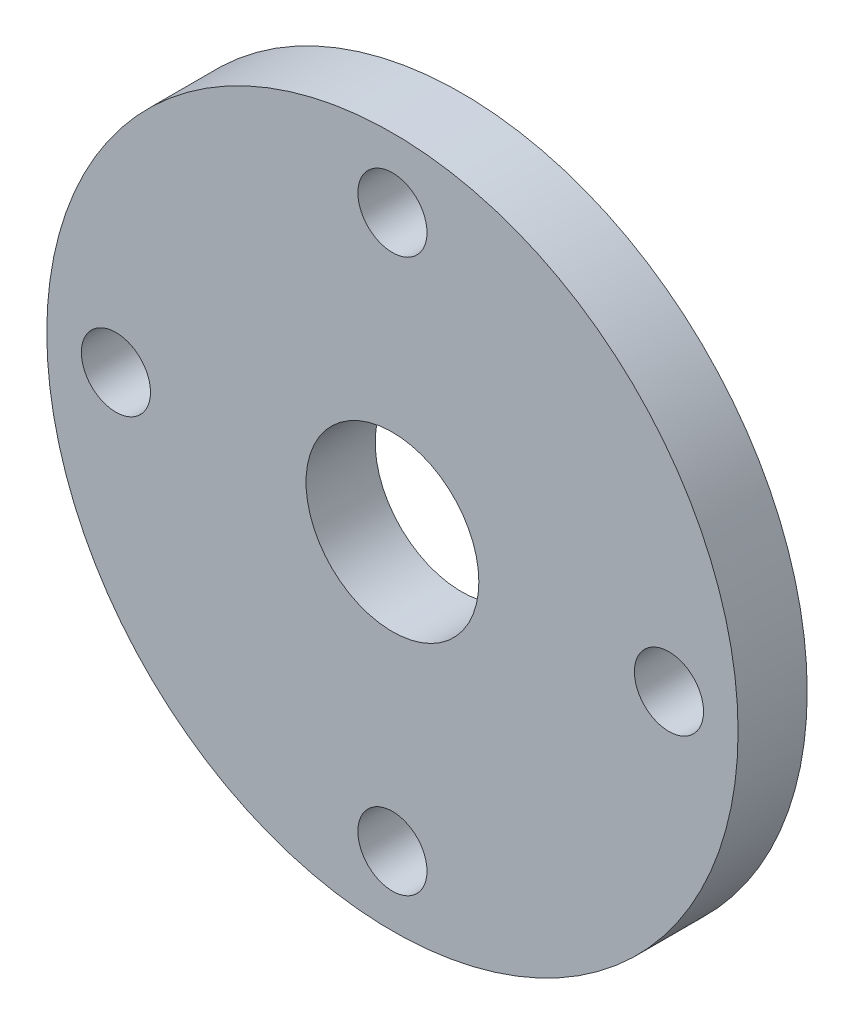
SolidWorks part; units mm, degrees
ref_plane "前视基准面" through (0, 0, 0) normal (0, 0, 1) x (1, 0, 0)
ref_plane "上视基准面" through (0, 0, 0) normal (0, 1, 0) x (1, 0, 0)
ref_plane "右视基准面" through (0, 0, 0) normal (1, 0, 0) x (0, 0, -1)
sketch "草图1" plane through (0, 0, 0) normal (0, 0, 1) x (1, 0, 0)
  line L0 (0, 0) -> (-4, 0) construction
  circle A0 centre (-4, 0) radius 0.5
  circle A1 centre (0, 0) radius 1.25
  circle A2 centre (0, 4) radius 0.5
  circle A3 centre (4, 0) radius 0.5
  circle A4 centre (0, -4) radius 0.5
  circle A5 centre (0, 0) radius 5
  point P14 (0, 0)
  dimension "D2" = 1
  dimension "D3" = 2.5
  dimension "D5" = 10
  dimension "D1" = 4
  dimension "D4" = 4
extrude "凸台-拉伸1" add sketch "草图1" along normal blind 1
